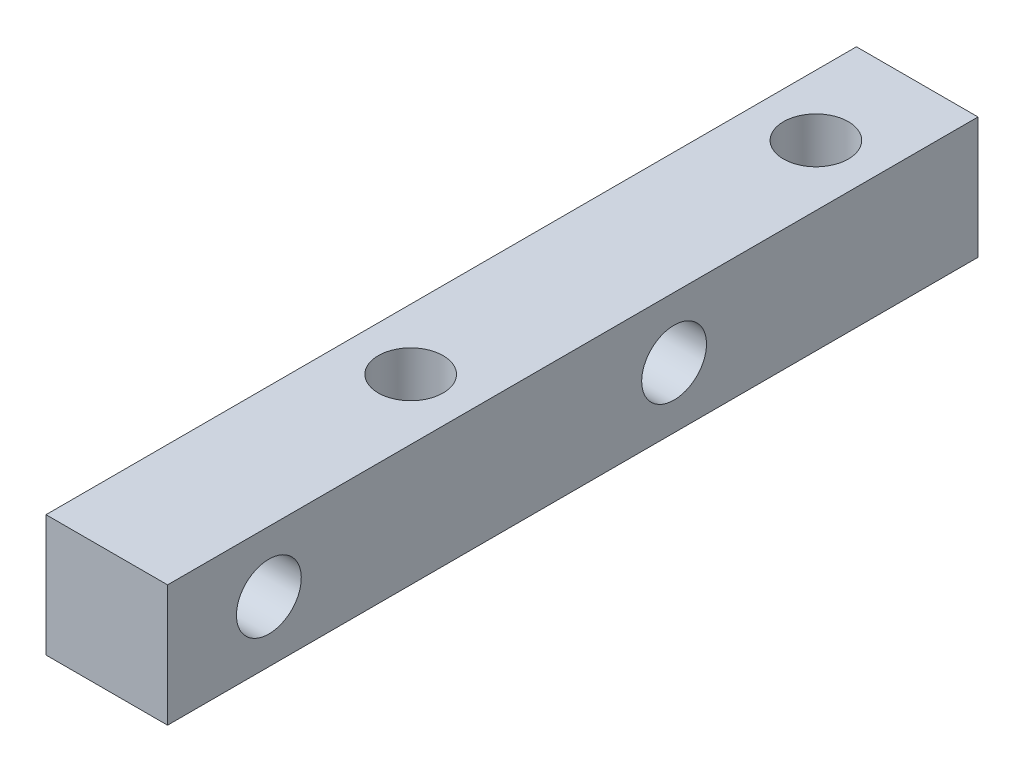
SolidWorks part; units mm, degrees
ref_plane "前视基准面" through (0, 0, 0) normal (0, 0, 1) x (1, 0, 0)
ref_plane "上视基准面" through (0, 0, 0) normal (0, 1, 0) x (1, 0, 0)
ref_plane "右视基准面" through (0, 0, 0) normal (1, 0, 0) x (0, 0, -1)
other "Configuration Table"
sketch "草图1" plane through (0, 0, 0) normal (0, 0, 1) x (1, 0, 0)
  line L1 (0, 0) -> (6, 0)
  line L2 (0, 0) -> (0, -6)
  line L3 (0, -6) -> (6, -6)
  line L4 (6, 0) -> (6, -6)
  dimension "D1" = 6
  dimension "D2" = 6
extrude "凸台-拉伸1" add sketch "草图1" along normal blind 40
sketch "草图2" plane through (6, 0, 0) normal (1, 0, 0) x (0, 0, -1)
  line L0 (-40, -3) -> (0, -3) construction
  line L1 (-40, -6) -> (-40, 0) construction
  line L2 (0, -6) -> (0, 0) construction
  line L7 (0, -6) -> (0, 0)
  line L8 (0, 0) -> (-40, 0)
  line L9 (-40, 0) -> (-40, -6)
  line L10 (-40, -6) -> (0, -6)
  line L11 (0, -6) -> (0, 0)
  line L12 (0, 0) -> (-40, 0)
  line L13 (-40, 0) -> (-40, -6)
  line L14 (-40, -6) -> (0, -6)
  circle A0 centre (-35, -3) radius 1.6
  circle A1 centre (-15, -3) radius 1.6
  dimension "D3" = 20
  dimension "D4" = 3.2
  dimension "D1" = 0
  dimension "D2" = 5
extrude "切除-拉伸1" cut sketch "草图2" against normal mid plane 48 contours A0 | A1
sketch "草图3" plane through (0, 0, 0) normal (0, 1, 0) x (1, 0, 0)
  line L0 (3, 0) -> (3, -40) construction
  line L1 (6, 0) -> (0, 0) construction
  line L2 (6, -40) -> (0, -40) construction
  circle A0 centre (3, -5) radius 1.6
  circle A1 centre (3, -25) radius 1.6
  dimension "D3" = 3.2
  dimension "D1" = 5
  dimension "D2" = 20
extrude "切除-拉伸2" cut sketch "草图3" against normal mid plane 48
equation "\"20、\"=10"
